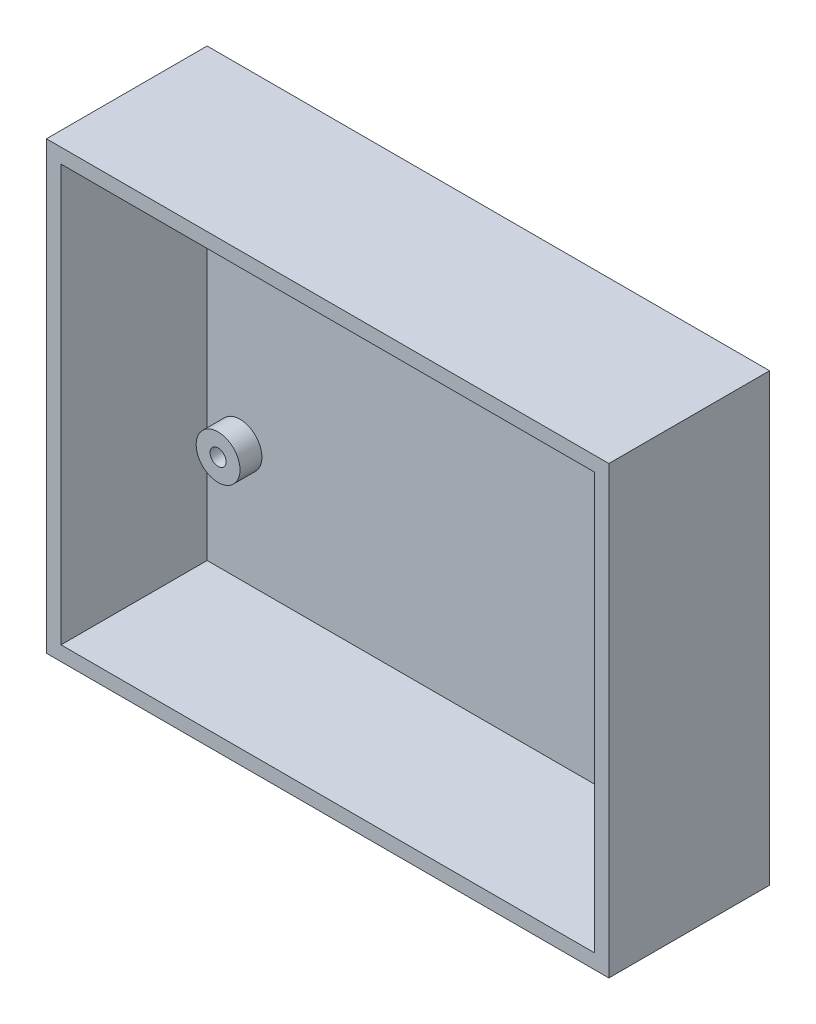
SolidWorks part; units mm, degrees
ref_plane "前视基准面" through (0, 0, 0) normal (0, 0, 1) x (1, 0, 0)
ref_plane "上视基准面" through (0, 0, 0) normal (0, 1, 0) x (1, 0, 0)
ref_plane "右视基准面" through (0, 0, 0) normal (1, 0, 0) x (0, 0, -1)
other "Configuration Table"
sketch "草图1" plane through (0, 0, 0) normal (0, 0, 1) x (1, 0, 0)
  line L1 (0, 0) -> (77, 0)
  line L2 (0, 0) -> (0, 61)
  line L3 (0, 61) -> (77, 61)
  line L4 (77, 0) -> (77, 61)
extrude "凸台-拉伸1" add sketch "草图1" along normal blind 22
sketch "草图2" plane through (0, 0, 0) normal (0, 0, 1) x (1, 0, 0)
  line L1 (2, 2) -> (75, 2)
  line L2 (2, 2) -> (2, 59)
  line L3 (2, 59) -> (75, 59)
  line L4 (75, 2) -> (75, 59)
extrude "切除-拉伸1" cut sketch "草图2" along normal through all
sketch "草图3" plane through (0, 0, 0) normal (0, 0, 1) x (1, 0, 0)
  line L1 (0, 0) -> (77, 0)
  line L2 (0, 0) -> (0, 61)
  line L3 (0, 61) -> (77, 61)
  line L4 (77, 0) -> (77, 61)
extrude "凸台-拉伸2" add sketch "草图3" along normal blind 2
sketch "草图4" plane through (0, 0, 0) normal (0, 0, 1) x (1, 0, 0)
  circle A0 centre (6.5, 18) radius 3
  circle A1 centre (70.5, 18) radius 3
  circle A2 centre (6.5, 54) radius 3
  circle A3 centre (70.5, 54) radius 3
extrude "凸台-拉伸3" add sketch "草图4" along normal blind 5
sketch "草图5" plane through (0, 0, 0) normal (0, 0, 1) x (1, 0, 0)
  circle A0 centre (6.5, 18) radius 1.1
  circle A1 centre (70.5, 18) radius 1.1
  circle A2 centre (6.5, 54) radius 1.1
  circle A3 centre (70.5, 54) radius 1.1
extrude "切除-拉伸2" cut sketch "草图5" along normal through all
